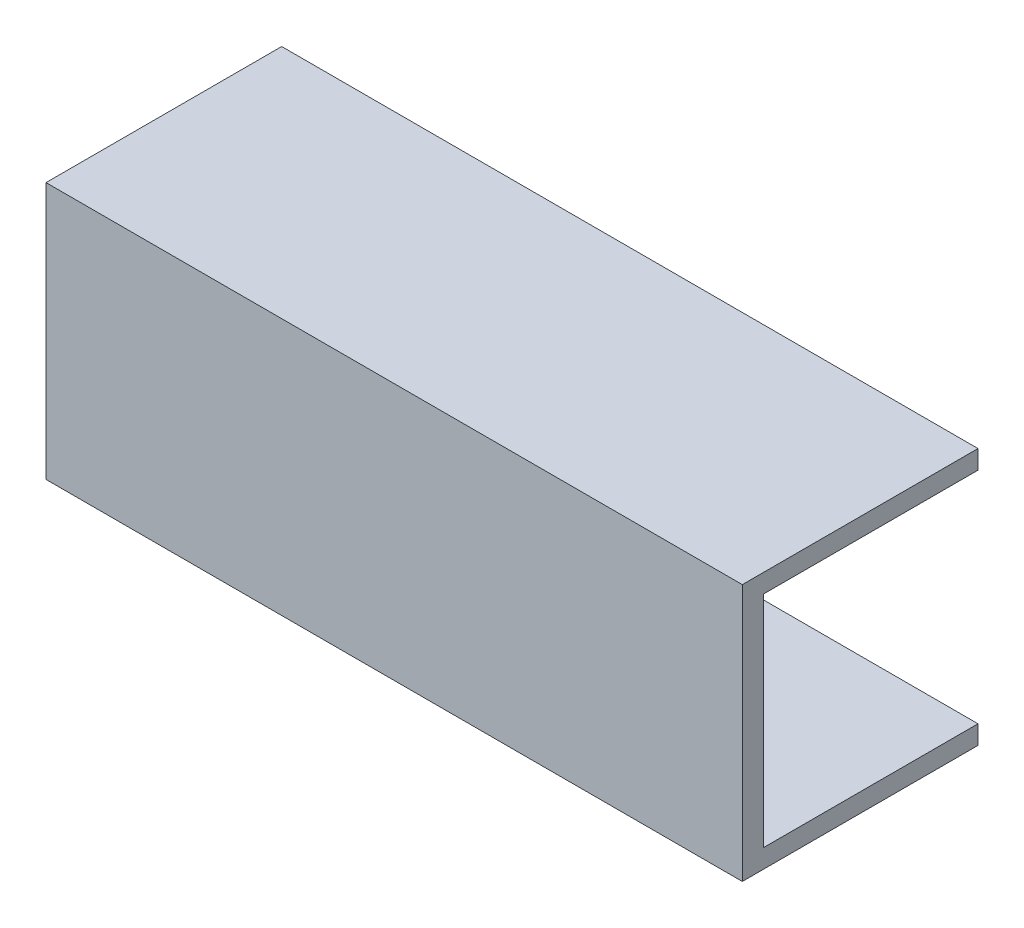
SolidWorks part; units mm, degrees
ref_plane "前视基准面" through (0, 0, 0) normal (0, 0, 1) x (1, 0, 0)
ref_plane "上视基准面" through (0, 0, 0) normal (0, 1, 0) x (1, 0, 0)
ref_plane "右视基准面" through (0, 0, 0) normal (1, 0, 0) x (0, 0, -1)
sketch "草图1" plane through (0, 0, 0) normal (0, 1, 0) x (1, 0, 0)
  line L1 (-34.2568, 15.5811) -> (30.7432, 15.5811)
  line L2 (-34.2568, 15.5811) -> (-34.2568, -6.4189)
  line L3 (-34.2568, -6.4189) -> (30.7432, -6.4189)
  line L4 (30.7432, 15.5811) -> (30.7432, -6.4189)
  dimension "D1" = 65
  dimension "D2" = 22
extrude "凸台-拉伸1" add sketch "草图1" along normal blind 24
sketch "草图2" plane through (-34.2568, 0, 0) normal (-1, 0, 0) x (0, 0, 1)
  line L0 (-15.5811, 24) -> (-15.5811, 0) construction
  line L1 (-15.5811, 22.25) -> (4.4189, 22.25)
  line L2 (-15.5811, 22.25) -> (-15.5811, 1.75)
  line L3 (-15.5811, 1.75) -> (4.4189, 1.75)
  line L4 (4.4189, 22.25) -> (4.4189, 1.75)
  line L5 (6.4189, 24) -> (6.4189, 0) construction
  line L6 (-15.5811, 24) -> (6.4189, 24) construction
  line L7 (-15.5811, 0) -> (6.4189, 0) construction
  dimension "D1" = 2
  dimension "D2" = 1.75
  dimension "D3" = 1.75
extrude "切除-拉伸1" cut sketch "草图2" against normal through all
